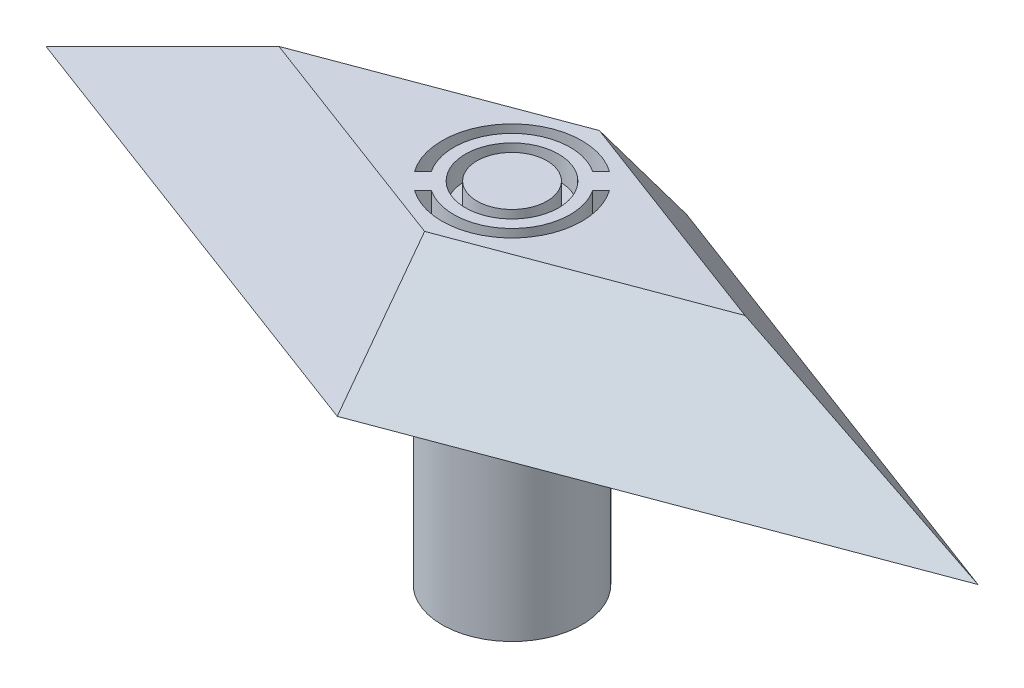
SolidWorks part; units mm, degrees
ref_plane "Front Plane" through (0, 0, 0) normal (0, 0, 1) x (1, 0, 0)
ref_plane "Top Plane" through (0, 0, 0) normal (0, 1, 0) x (1, 0, 0)
ref_plane "Right Plane" through (0, 0, 0) normal (1, 0, 0) x (0, 0, -1)
sketch "Sketch1" plane through (0, 0, 0) normal (0, 1, 0) x (1, 0, 0)
  line L0 (-20, 0) -> (0, 7.5)
  line L5 (-10, -3.75) -> (10, 3.75) construction
  line L6 (-10, 3.75) -> (10, -3.75) construction
  line L7 (0, 7.5) -> (20, 0)
  line L8 (20, 0) -> (0, -7.5)
  line L9 (0, -7.5) -> (-20, 0)
  point P0 (0, 0)
ref_plane "Plane1" through (0, 5, 0) normal (0, -1, 0) x (-1, 0, 0)
sketch "Sketch3" plane through (0, 5, 0) normal (0, -1, 0) x (-1, 0, 0)
  line L0 (0, 3.75) -> (-10, 0)
  line L5 (-5, 1.875) -> (5, -1.875) construction
  line L6 (-5, -1.875) -> (5, 1.875) construction
  line L7 (-10, 0) -> (0, -3.75)
  line L8 (0, -3.75) -> (10, 0)
  line L9 (10, 0) -> (0, 3.75)
  point P0 (0, 0)
sketch "Sketch4" plane through (0, 0, 0) normal (0, 0, 1) x (1, 0, 0)
  line L0 (-20, 0) -> (10, 5)
  line L1 (20, 0) -> (10, 5)
  line L2 (20, 0) -> (0, 0) construction
  line L3 (0, 0) -> (20, 0) construction
  line L4 (0, 5) -> (-10, 5) construction
  line L5 (-8.2501, 5) -> (8.2501, 5) construction
loft "Loft1" add profiles "Sketch1", "Sketch3"
sketch "Sketch5" plane through (0, 0, 0) normal (0, 1, 0) x (1, 0, 0)
  line L0 (-2, -2.2361) -> (-2, 2.2361)
  arc A0 (-2, -2.2361) -> (-2, 2.2361) centre (0, 0) ccw
  dimension "D1" = 2
extrude "Boss-Extrude1" add sketch "Sketch5" against normal blind 10
sketch "Sketch6" plane through (0, 5, 0) normal (0, -1, 0) x (-1, 0, 0)
  line L0 (-1.7381, 2.4452) -> (-1.3785, 2.0856)
  line L1 (-2.4452, 1.7381) -> (-2.0856, 1.3785)
  line L3 (2.0856, -1.3785) -> (2.4452, -1.7381)
  line L4 (1.3785, -2.0856) -> (1.7381, -2.4452)
  arc A0 (2.4452, -1.7381) -> (-1.7381, 2.4452) centre (0, 0) ccw
  arc A1 (2.0856, -1.3785) -> (-1.3785, 2.0856) centre (0, 0) ccw
  arc A2 (-2.4452, 1.7381) -> (1.7381, -2.4452) centre (0, 0) ccw
  arc A3 (-2.0856, 1.3785) -> (1.3785, -2.0856) centre (0, 0) ccw
  dimension "D1" = 1
  dimension "D2" = 0.5
extrude "Cut-Extrude1" cut sketch "Sketch6" along normal blind 1
sketch "Sketch7" plane through (0, 5, 0) normal (0, -1, 0) x (-1, 0, 0)
  circle A0 centre (0, 0) radius 2
  circle A1 centre (0, 0) radius 1.5
extrude "Cut-Extrude2" cut sketch "Sketch7" along normal blind 1
